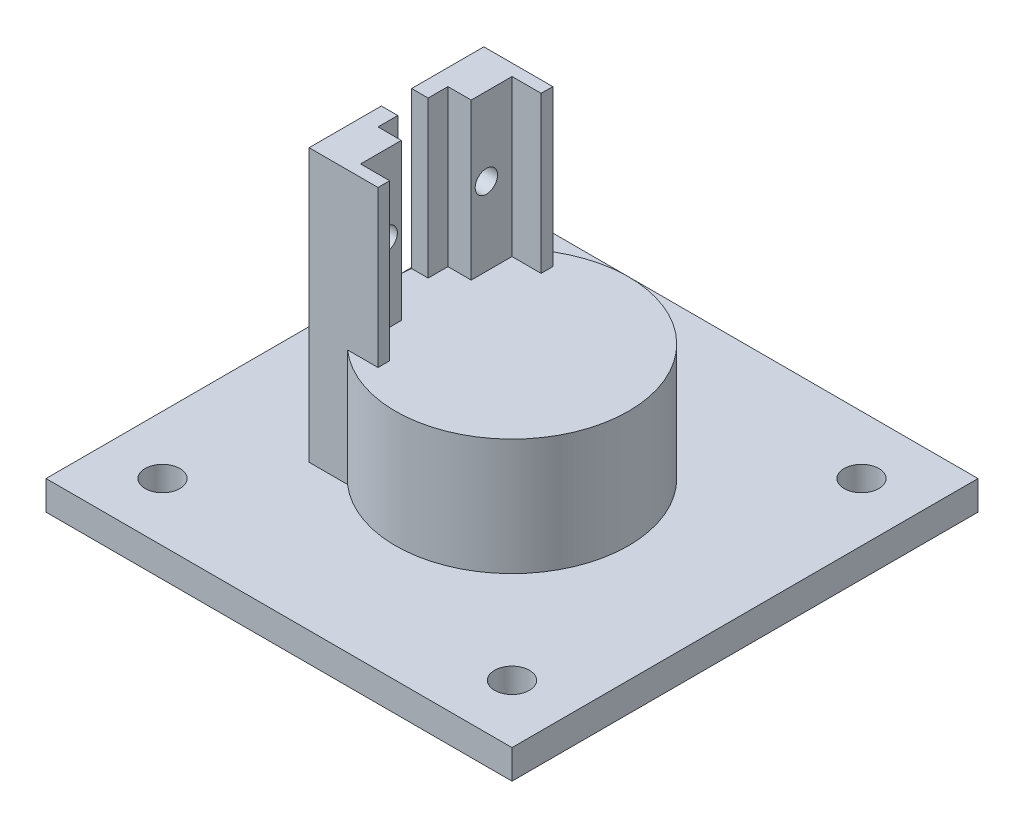
SolidWorks part; units mm, degrees
ref_plane "Front Plane" through (0, 0, 0) normal (0, 0, 1) x (1, 0, 0)
ref_plane "Top Plane" through (0, 0, 0) normal (0, 1, 0) x (1, 0, 0)
ref_plane "Right Plane" through (0, 0, 0) normal (1, 0, 0) x (0, 0, -1)
sketch "Sketch1" plane through (0, 0, 0) normal (0, 1, 0) x (1, 0, 0)
  circle A0 centre (0, 0) radius 12.7
  dimension "D1" = 25.4
extrude "Boss-Extrude1" add sketch "Sketch1" along normal blind 12.7
sketch "Sketch7" plane through (0, 12.7, 0) normal (0, 1, 0) x (1, 0, 0)
  line L0 (-12.7, -9.525) -> (-12.7, 9.525)
  line L1 (-12.7, 9.525) -> (-5.08, 9.525)
  line L2 (-5.08, 9.525) -> (-5.08, 8.255)
  line L5 (-5.08, 8.255) -> (-8.255, 8.255)
  line L6 (-8.255, 8.255) -> (-8.255, -8.255)
  line L7 (-8.255, -8.255) -> (-5.08, -8.255)
  line L10 (-5.08, -8.255) -> (-5.08, -9.525)
  line L11 (-5.08, -9.525) -> (-12.7, -9.525)
  circle A0 centre (0, 0) radius 12.7 construction
  dimension "D8" = 12.7
  dimension "D2" = 3.175
  dimension "D3" = 7.62
  dimension "D5" = 16.51
  dimension "D6" = 19.05
  dimension "D7" = 7.62
  dimension "D9" = 1.27
  dimension "D12" = 9.525
extrude "Boss-Extrude2" add sketch "Sketch7" along normal blind 17
sketch "Sketch8" plane through (0, 29.7, 0) normal (0, 1, 0) x (1, 0, 0)
  line L0 (-8.255, 8.255) -> (-8.255, -8.255) construction
  line L1 (-8.255, 3.81) -> (-10.795, 3.81)
  line L2 (-8.255, 3.81) -> (-8.255, -3.81)
  line L3 (-8.255, -3.81) -> (-10.795, -3.81)
  line L4 (-10.795, 3.81) -> (-10.795, -3.81)
  line L5 (0, 0) -> (-17.6466, 0) construction
  line L10 (-10.795, 1.651) -> (-12.7, 1.651)
  line L12 (-10.795, -1.651) -> (-12.7, -1.651)
  line L13 (-12.7, 1.651) -> (-12.7, -1.651)
  arc A0 (-8.4003, 9.525) -> (-8.4003, -9.525) centre (0, 0) ccw construction
  line M6 (-8.255, -8.255) -> (-8.255, 8.255)
  arc M12 (-8.4003, 9.525) -> (-8.4003, -9.525) centre (0, 0) ccw
  dimension "D1" = 7.62
  dimension "D2" = 3.81
  dimension "D3" = 3.302
  dimension "D4" = 1.651
  dimension "D5" = 12.7
  dimension "D6" = 2.54
extrude "Cut-Extrude3" cut sketch "Sketch8" against normal up to surface (17 mm away) contours L4 L5 L12 M12 | L5 L4 L10 M12 | L5 L2 L1 L4 | L5 L4 L3 M6
sketch "Sketch13" plane through (0, 29.7, 0) normal (0, 1, 0) x (1, 0, 0)
  line L0 (-12.5922, -9.525) -> (-8.4003, -9.525)
  line L1 (-12.5922, -1.651) -> (-12.5922, -9.525)
  line L2 (-12.5922, 9.525) -> (-8.4003, 9.525)
  line L3 (-12.5922, 1.651) -> (-12.5922, 9.525)
  line L5 (-5.08, -9.525) -> (-8.4003, -9.525) construction
  arc A0 (-8.4003, 9.525) -> (-8.4003, -9.525) centre (0, 0) ccw
  arc A1 (-12.5922, -1.651) -> (-8.4003, -9.525) centre (0, 0) ccw construction
  arc A3 (-8.4003, -9.525) -> (-8.4003, 9.525) centre (0, 0) ccw construction
  arc M10 (-8.4003, 9.525) -> (-12.5922, 1.651) centre (0, 0) ccw
  dimension "D1" = 0
extrude "Boss-Extrude4" add sketch "Sketch13" against normal up to surface (29.7 mm away) contours L3 L2 M10 | A0 L1 L0 up to face at (0, 0, 12.7)
hole_wizard "#2 Clearance Hole1" positions "Sketch10" profile "Sketch11" hole size "#2" standard "ANSI Inch"
sketch "Sketch10" plane through (-8.255, 0, 0) normal (1, 0, 0) x (0, 0, -1)
  line L0 (-3.81, 12.7) -> (-8.255, 12.7) construction
  line L1 (8.255, 12.7) -> (3.81, 12.7) construction
  line L2 (12.7, 12.7) -> (-12.7, 12.7) construction
  point P0 (-5.46, 21.2)
  point P2 (5.46, 21.2)
  point P9 (0, 12.7)
  dimension "D1" = 8.5
  dimension "D2" = 8.5
  dimension "D3" = 10.92
  dimension "D4" = 5.46
sketch "Sketch11" plane through (-8.255, 21.2, 5.46) normal (0, 1, 0) x (0, 0, -1)
  line L0 (0, 0) -> (0, 26.1326)
  line L1 (0, 26.1326) -> (1.2192, 25.4)
  line L2 (1.2192, 25.4) -> (1.2192, 0)
  line L5 (1.2192, 0) -> (0, 0)
  line L10 (0, 26.1326) -> (-1.2192, 25.4) construction
  line L11 (0, -6.35) -> (0, 107.95) construction
  dimension "Hole Dia." = 2.4384
  dimension "Hole Depth" = 25.4
  dimension "Drill Angle" = 118
sketch "Sketch14" plane through (0, 0, 0) normal (0, -1, 0) x (1, 0, 0)
  line L1 (25.4, 25.4) -> (-25.4, 25.4)
  line L2 (25.4, 25.4) -> (25.4, -25.4)
  line L3 (25.4, -25.4) -> (-25.4, -25.4)
  line L4 (-25.4, 25.4) -> (-25.4, -25.4)
  line L5 (25.4, 25.4) -> (-25.4, -25.4) construction
  line L6 (25.4, -25.4) -> (-25.4, 25.4) construction
  point P0 (0, 0)
  dimension "D1" = 50.8
  dimension "D2" = 50.8
extrude "Boss-Extrude7" add sketch "Sketch14" along normal blind 3.175
hole_wizard "#6 Clearance Hole1" positions "Sketch17" profile "Sketch18" hole size "#6" standard "ANSI Inch"
sketch "Sketch17" plane through (0, -3.175, 0) normal (0, -1, 0) x (-1, 0, 0)
  line L0 (25.4, -25.4) -> (25.4, 25.4) construction
  line L1 (-25.4, -25.4) -> (25.4, -25.4) construction
  line L2 (-25.4, 25.4) -> (-25.4, -25.4) construction
  line L3 (25.4, 25.4) -> (-25.4, 25.4) construction
  point P0 (19.05, -19.05)
  point P2 (-19.05, -19.05)
  point P4 (-19.05, 19.05)
  point P6 (19.05, 19.05)
  dimension "D1" = 6.35
  dimension "D2" = 6.35
  dimension "D3" = 6.35
  dimension "D4" = 6.35
  dimension "D5" = 6.35
  dimension "D6" = 6.35
  dimension "D7" = 6.35
  dimension "D8" = 6.35
sketch "Sketch18" plane through (-19.05, -3.175, 19.05) normal (1, 0, 0) x (0, 0, -1)
  line L0 (0, 0) -> (0, 26.5408)
  line L1 (0, 26.5408) -> (1.8986, 25.4)
  line L2 (1.8986, 25.4) -> (1.8986, 0)
  line L5 (1.8986, 0) -> (0, 0)
  line L10 (0, 26.5408) -> (-1.8987, 25.4) construction
  line L11 (0, -6.35) -> (0, 107.95) construction
  dimension "Hole Dia." = 3.7973
  dimension "Hole Depth" = 25.4
  dimension "Drill Angle" = 118
